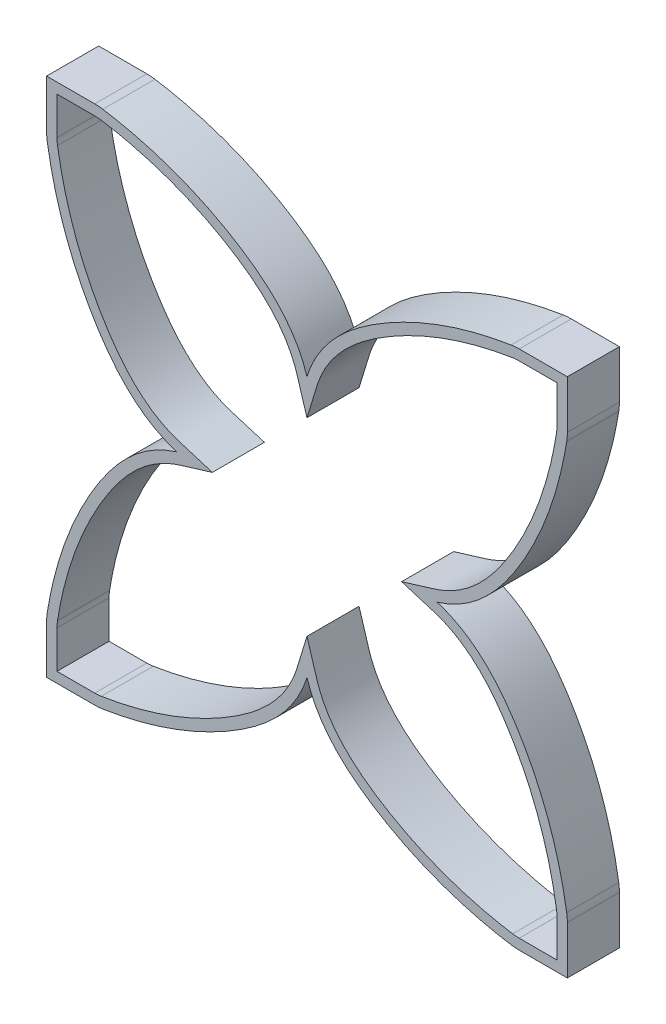
SolidWorks part; units mm, degrees
ref_plane "Front Plane" through (0, 0, 0) normal (0, 0, 1) x (1, 0, 0)
ref_plane "Top Plane" through (0, 0, 0) normal (0, 1, 0) x (1, 0, 0)
ref_plane "Right Plane" through (0, 0, 0) normal (1, 0, 0) x (0, 0, -1)
sketch "Sketch1" plane through (0, 0, 0) normal (0, 0, 1) x (1, 0, 0)
  line L0 (2, -2) -> (2, -9.2421)
  line L6 (2, -98) -> (2, -90.7579)
  line L7 (2, -98) -> (9.2421, -98)
  line L8 (98, -98) -> (90.7579, -98)
  line L9 (98, -98) -> (98, -90.7579)
  line L12 (98, -2) -> (98, -9.2421)
  line L13 (98, -2) -> (90.7579, -2)
  line L14 (2, -2) -> (9.2421, -2)
  line L16 (0, 0) -> (0, -9.2421) construction
  line L17 (0, 0) -> (0, -9.2421)
  line L18 (0, 0) -> (9.2421, 0) construction
  line L19 (0, 0) -> (9.2421, 0)
  line L20 (100, 0) -> (90.7579, 0) construction
  line L21 (100, 0) -> (100, -9.2421) construction
  line L23 (100, 0) -> (90.7579, 0)
  line L24 (100, 0) -> (100, -9.2421)
  line L26 (100, -100) -> (100, -90.7579) construction
  line L27 (100, -100) -> (90.7579, -100) construction
  line L28 (0, -100) -> (9.2421, -100) construction
  line L29 (0, -100) -> (0, -90.7579) construction
  line L35 (100, -100) -> (100, -90.7579)
  line L36 (100, -100) -> (90.7579, -100)
  line L37 (0, -100) -> (9.2421, -100)
  line L38 (0, -100) -> (0, -90.7579)
  arc A0 (0.1226, -10.8031) -> (0, -9.2421) centre (10, -9.2421) cw
  arc A1 (10.8031, -0.1226) -> (9.2421, 0) centre (9.2421, -10) ccw
  arc A2 (89.1969, -0.1226) -> (90.7579, 0) centre (90.7579, -10) cw
  arc A3 (99.8774, -10.8031) -> (100, -9.2421) centre (90, -9.2421) ccw
  arc A4 (99.8774, -89.1969) -> (100, -90.7579) centre (90, -90.7579) cw
  arc A5 (89.1969, -99.8774) -> (90.7579, -100) centre (90.7579, -90) ccw
  arc A6 (10.8031, -99.8774) -> (9.2421, -100) centre (9.2421, -90) cw
  arc A7 (0.1226, -89.1969) -> (0, -90.7579) centre (10, -90.7579) ccw
  arc A8 (2.0981, -10.4909) -> (2, -9.2421) centre (10, -9.2421) cw
  arc A9 (2.0981, -89.5091) -> (2, -90.7579) centre (10, -90.7579) ccw
  arc A10 (10.4909, -97.9019) -> (9.2421, -98) centre (9.2421, -90) cw
  arc A11 (89.5091, -97.9019) -> (90.7579, -98) centre (90.7579, -90) ccw
  arc A12 (97.9019, -89.5091) -> (98, -90.7579) centre (90, -90.7579) cw
  arc A13 (97.9019, -10.4909) -> (98, -9.2421) centre (90, -9.2421) ccw
  arc A14 (89.5091, -2.0981) -> (90.7579, -2) centre (90.7579, -10) cw
  arc A15 (10.4909, -2.0981) -> (9.2421, -2) centre (9.2421, -10) ccw
  spline S0 degree 3 poles (0.1226, -10.8031) (0.6859, -14.3675) (2.7115, -23.1403) (9.2844, -37.9873) (17.8012, -47.7947) (25, -50) knots 0.016476 0.016476 0.016476 0.016476 0.236061 0.563585 1 1 1 1
  spline S1 degree 3 poles (10.8031, -0.1226) (14.3675, -0.6859) (23.1403, -2.7115) (37.9873, -9.2844) (47.7947, -17.8012) (50, -25) knots 0.016476 0.016476 0.016476 0.016476 0.236061 0.563585 1 1 1 1
  spline S2 degree 3 poles (89.1969, -0.1226) (85.6325, -0.6859) (76.8597, -2.7115) (62.0127, -9.2844) (52.2053, -17.8012) (50, -25) knots 0.016476 0.016476 0.016476 0.016476 0.236061 0.563585 1 1 1 1
  spline S3 degree 3 poles (99.8774, -10.8031) (99.3141, -14.3675) (97.2885, -23.1403) (90.7156, -37.9873) (82.1988, -47.7947) (75, -50) knots 0.016476 0.016476 0.016476 0.016476 0.236061 0.563585 1 1 1 1
  spline S4 degree 3 poles (99.8774, -89.1969) (99.3141, -85.6325) (97.2885, -76.8597) (90.7156, -62.0127) (82.1988, -52.2053) (75, -50) knots 0.016476 0.016476 0.016476 0.016476 0.236061 0.563585 1 1 1 1
  spline S5 degree 3 poles (89.1969, -99.8774) (85.6325, -99.3141) (76.8597, -97.2885) (62.0127, -90.7156) (52.2053, -82.1988) (50, -75) knots 0.016476 0.016476 0.016476 0.016476 0.236061 0.563585 1 1 1 1
  spline S6 degree 3 poles (10.8031, -99.8774) (14.3675, -99.3141) (23.1403, -97.2885) (37.9873, -90.7156) (47.7947, -82.1988) (50, -75) knots 0.016476 0.016476 0.016476 0.016476 0.236061 0.563585 1 1 1 1
  spline S7 degree 3 poles (0.1226, -89.1969) (0.6859, -85.6325) (2.7115, -76.8597) (9.2844, -62.0127) (17.8012, -52.2053) (25, -50) knots 0.016476 0.016476 0.016476 0.016476 0.236061 0.563585 1 1 1 1
  spline S8 degree 1 poles (2.0981, -10.4909) (31.828, -50) knots 0 0 1 1 construction
  spline S9 degree 1 poles (2.0981, -89.5091) (31.828, -50) knots 0 0 1 1 construction
  spline S10 degree 1 poles (10.4909, -97.9019) (50, -68.172) knots 0 0 1 1 construction
  spline S11 degree 1 poles (89.5091, -97.9019) (50, -68.172) knots 0 0 1 1 construction
  spline S12 degree 1 poles (97.9019, -89.5091) (68.172, -50) knots 0 0 1 1 construction
  spline S13 degree 1 poles (97.9019, -10.4909) (68.172, -50) knots 0 0 1 1 construction
  spline S14 degree 1 poles (89.5091, -2.0981) (50, -31.828) knots 0 0 1 1 construction
  spline S15 degree 1 poles (10.4909, -2.0981) (50, -31.828) knots 0 0 1 1 construction
  spline S16 degree 3 poles (2.0981, -10.4909) (2.4441, -12.6802) (3.3317, -17.0351) (5.26, -23.3893) (7.8014, -29.5134) (10.983, -35.3729) (14.1492, -39.906) (17.0593, -43.021) (19.4512, -45.0498) (21.6415, -46.4411) (23.5233, -47.3501) (24.6477, -47.7841) (25.4053, -48.0331) (25.9578, -48.2013) (26.971, -48.5123) (28.9642, -49.1225) (30.684, -49.6495) (31.828, -50) knots 0.016476 0.016476 0.016476 0.016476 0.155184 0.293892 0.4326 0.571308 0.710016 0.77937 0.848724 0.918078 0.952755 0.987432 0.996102 1.004771 1.022109 1.056786 1.12614 1.12614 1.12614 1.12614
  spline S17 degree 3 poles (31.828, -50) (30.684, -50.3505) (28.9642, -50.8775) (26.971, -51.4877) (25.9578, -51.7987) (25.4053, -51.9669) (24.6477, -52.2159) (23.5233, -52.6499) (21.6415, -53.5589) (19.4512, -54.9502) (17.0593, -56.979) (14.1492, -60.094) (10.983, -64.6271) (7.8014, -70.4866) (5.26, -76.6107) (3.3317, -82.9649) (2.4441, -87.3198) (2.0981, -89.5091) knots 0.016476 0.016476 0.016476 0.016476 0.08583 0.120507 0.137845 0.146515 0.155184 0.189861 0.224538 0.293892 0.363246 0.4326 0.571308 0.710016 0.848724 0.987432 1.12614 1.12614 1.12614 1.12614
  spline S18 degree 3 poles (10.4909, -97.9019) (12.6802, -97.5559) (17.0351, -96.6683) (23.3893, -94.74) (29.5134, -92.1986) (35.3729, -89.017) (39.906, -85.8508) (43.021, -82.9407) (45.0498, -80.5488) (46.4411, -78.3585) (47.3501, -76.4767) (47.7841, -75.3523) (48.0331, -74.5947) (48.2013, -74.0422) (48.5123, -73.029) (49.1225, -71.0358) (49.6495, -69.316) (50, -68.172) knots 0.016476 0.016476 0.016476 0.016476 0.155184 0.293892 0.4326 0.571308 0.710016 0.77937 0.848724 0.918078 0.952755 0.987432 0.996102 1.004771 1.022109 1.056786 1.12614 1.12614 1.12614 1.12614
  spline S19 degree 3 poles (50, -68.172) (50.3505, -69.316) (50.8775, -71.0358) (51.4877, -73.029) (51.7987, -74.0422) (51.9669, -74.5947) (52.2159, -75.3523) (52.6499, -76.4767) (53.5589, -78.3585) (54.9502, -80.5488) (56.979, -82.9407) (60.094, -85.8508) (64.6271, -89.017) (70.4866, -92.1986) (76.6107, -94.74) (82.9649, -96.6683) (87.3198, -97.5559) (89.5091, -97.9019) knots 0.016476 0.016476 0.016476 0.016476 0.08583 0.120507 0.137845 0.146515 0.155184 0.189861 0.224538 0.293892 0.363246 0.4326 0.571308 0.710016 0.848724 0.987432 1.12614 1.12614 1.12614 1.12614
  spline S20 degree 3 poles (97.9019, -89.5091) (97.5559, -87.3198) (96.6683, -82.9649) (94.74, -76.6107) (92.1986, -70.4866) (89.017, -64.6271) (85.8508, -60.094) (82.9407, -56.979) (80.5488, -54.9502) (78.3585, -53.5589) (76.4767, -52.6499) (75.3523, -52.2159) (74.5947, -51.9669) (74.0422, -51.7987) (73.029, -51.4877) (71.0358, -50.8775) (69.316, -50.3505) (68.172, -50) knots 0.016476 0.016476 0.016476 0.016476 0.155184 0.293892 0.4326 0.571308 0.710016 0.77937 0.848724 0.918078 0.952755 0.987432 0.996102 1.004771 1.022109 1.056786 1.12614 1.12614 1.12614 1.12614
  spline S21 degree 3 poles (68.172, -50) (69.316, -49.6495) (71.0358, -49.1225) (73.029, -48.5123) (74.0422, -48.2013) (74.5947, -48.0331) (75.3523, -47.7841) (76.4767, -47.3501) (78.3585, -46.4411) (80.5488, -45.0498) (82.9407, -43.021) (85.8508, -39.906) (89.017, -35.3729) (92.1986, -29.5134) (94.74, -23.3893) (96.6683, -17.0351) (97.5559, -12.6802) (97.9019, -10.4909) knots 0.016476 0.016476 0.016476 0.016476 0.08583 0.120507 0.137845 0.146515 0.155184 0.189861 0.224538 0.293892 0.363246 0.4326 0.571308 0.710016 0.848724 0.987432 1.12614 1.12614 1.12614 1.12614
  spline S22 degree 3 poles (89.5091, -2.0981) (87.3198, -2.4441) (82.9649, -3.3317) (76.6107, -5.26) (70.4866, -7.8014) (64.6271, -10.983) (60.094, -14.1492) (56.979, -17.0593) (54.9502, -19.4512) (53.5589, -21.6415) (52.6499, -23.5233) (52.2159, -24.6477) (51.9669, -25.4053) (51.7987, -25.9578) (51.4877, -26.971) (50.8775, -28.9642) (50.3505, -30.684) (50, -31.828) knots 0.016476 0.016476 0.016476 0.016476 0.155184 0.293892 0.4326 0.571308 0.710016 0.77937 0.848724 0.918078 0.952755 0.987432 0.996102 1.004771 1.022109 1.056786 1.12614 1.12614 1.12614 1.12614
  spline S23 degree 3 poles (50, -31.828) (49.6495, -30.684) (49.1225, -28.9642) (48.5123, -26.971) (48.2013, -25.9578) (48.0331, -25.4053) (47.7841, -24.6477) (47.3501, -23.5233) (46.4411, -21.6415) (45.0498, -19.4512) (43.021, -17.0593) (39.906, -14.1492) (35.3729, -10.983) (29.5134, -7.8014) (23.3893, -5.26) (17.0351, -3.3317) (12.6802, -2.4441) (10.4909, -2.0981) knots 0.016476 0.016476 0.016476 0.016476 0.08583 0.120507 0.137845 0.146515 0.155184 0.189861 0.224538 0.293892 0.363246 0.4326 0.571308 0.710016 0.848724 0.987432 1.12614 1.12614 1.12614 1.12614
  dimension "D1" = 10
  dimension "D2" = 2
extrude "Boss-Extrude1" add sketch "Sketch1" along normal blind 10
